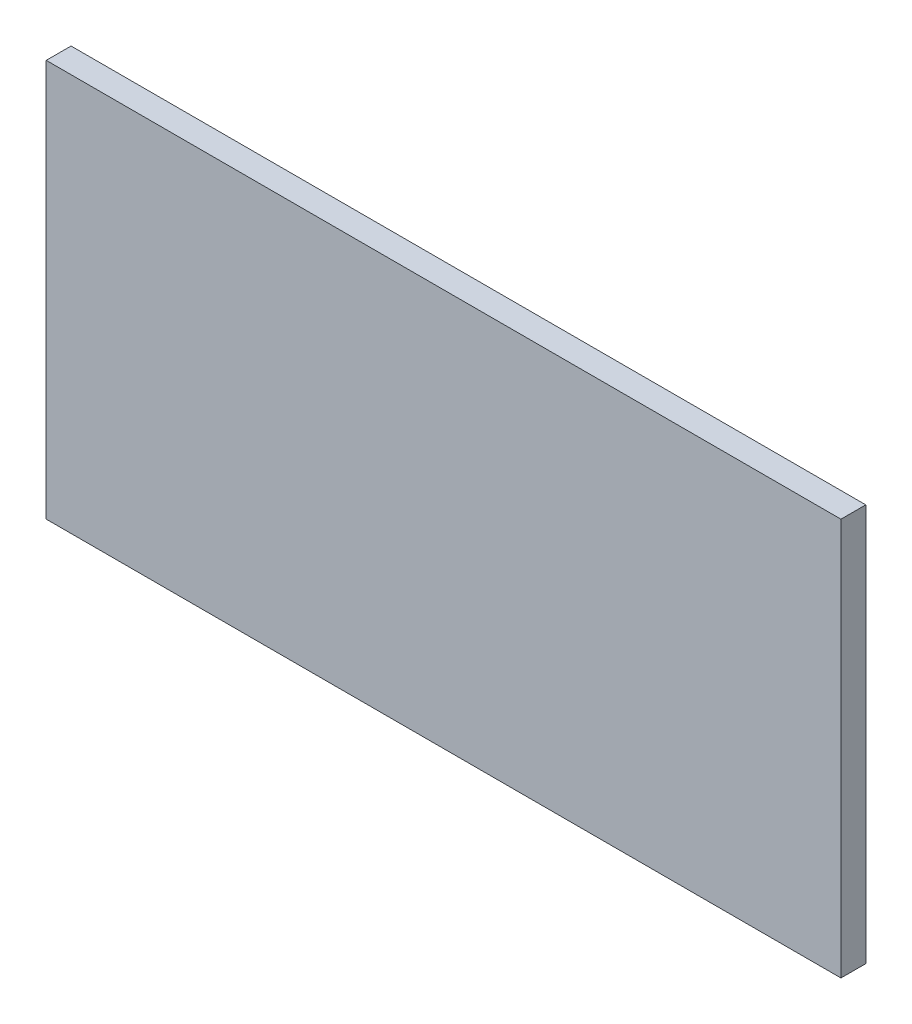
SolidWorks part; units mm, degrees
ref_plane "Alzado" through (0, 0, 0) normal (0, 0, 1) x (1, 0, 0)
ref_plane "Planta" through (0, 0, 0) normal (0, 1, 0) x (1, 0, 0)
ref_plane "Vista lateral" through (0, 0, 0) normal (1, 0, 0) x (0, 0, -1)
sketch "Croquis1" plane through (0, 0, 0) normal (0, 0, 1) x (1, 0, 0)
  line L1 (-40, 20) -> (40, 20)
  line L2 (-40, 20) -> (-40, -20)
  line L3 (-40, -20) -> (40, -20)
  line L4 (40, 20) -> (40, -20)
  line L5 (-40, 20) -> (40, -20) construction
  line L6 (-40, -20) -> (40, 20) construction
  point P0 (0, 0)
  dimension "D1" = 80
  dimension "D2" = 40
extrude "Saliente-Extruir1" add sketch "Croquis1" along normal blind 2.5
